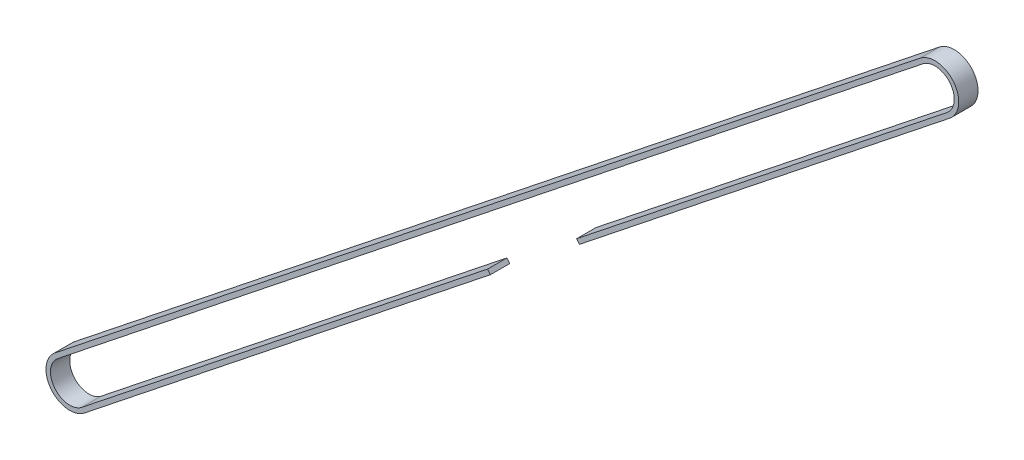
SolidWorks part; units mm, degrees
ref_plane "Спереди" through (0, 0, 0) normal (0, 0, 1) x (1, 0, 0)
ref_plane "Сверху" through (0, 0, 0) normal (0, 1, 0) x (1, 0, 0)
ref_plane "Справа" through (0, 0, 0) normal (1, 0, 0) x (0, 0, -1)
ref_plane "Плоскость1" through (0, 0, 0) normal (0, 0, -1) x (-1, 0, 0)
sketch "Эскиз1" plane through (0, 0, 0) normal (0, 0, -1) x (-1, 0, 0)
  line L0 (-265.4461, 218.715) -> (3.7341, 4.6965)
  line L1 (-3.7341, -4.6965) -> (-130, 95.6945)
  line L2 (-273.7855, 208.2262) -> (-158.5508, 116.6059)
  line L3 (4.6053, 5.7923) -> (-264.5748, 219.8109)
  line L4 (0, 0) -> (-269.1802, 214.0185) construction
  line L6 (-158.5508, 116.6059) -> (-157.6795, 117.7018)
  line L7 (-130.8713, 94.5986) -> (-130, 95.6945)
  line L11 (-157.6795, 117.7018) -> (-272.9142, 209.3221)
  line L12 (-130.8713, 94.5986) -> (-4.6053, -5.7923)
  arc A0 (3.7341, 4.6965) -> (-3.7341, -4.6965) centre (0, 0) cw
  arc A1 (-272.9142, 209.3221) -> (-265.4461, 218.715) centre (-269.1802, 214.0185) cw
  arc A2 (-264.5748, 219.8109) -> (-273.7855, 208.2262) centre (-269.1802, 214.0185) ccw
  arc A3 (-4.6053, -5.7923) -> (4.6053, 5.7923) centre (0, 0) ccw
  dimension "D1" = 6
  dimension "D2" = 7.4
  dimension "D3" = 343.8923
  dimension "D4" = 3.7341
  dimension "D5" = 130
  dimension "D6" = 157.6795
extrude "Бобышка-Вытянуть1" add sketch "Эскиз1" against normal blind 6
